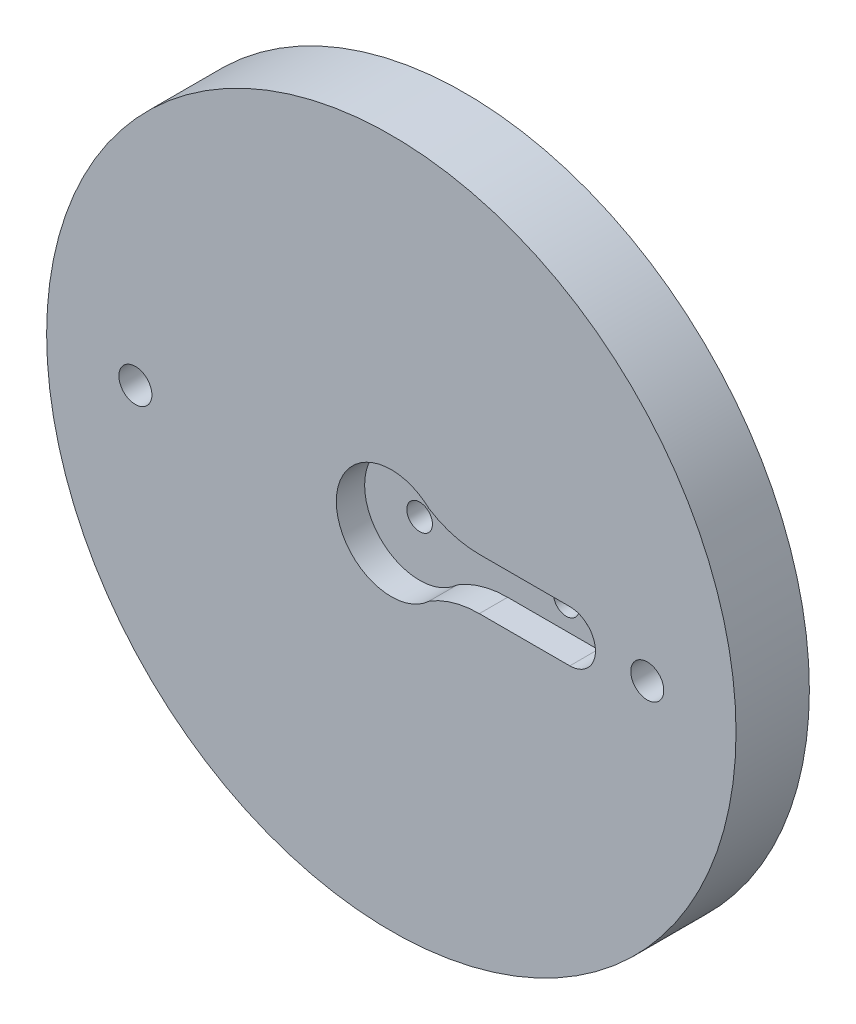
SolidWorks part; units mm, degrees
ref_plane "Front Plane" through (0, 0, 0) normal (1, 0, 0) x (0, 1, 0)
ref_plane "Top Plane" through (0, 0, 0) normal (0, 0, 1) x (0, 1, 0)
ref_plane "Right Plane" through (0, 0, 0) normal (0, 1, 0) x (-1, 0, 0)
sketch "Sketch1" plane through (0, 0, 0) normal (0, 0, 1) x (0, 1, 0)
  line L0 (0, 47) -> (0, -47) construction
  line L1 (-5.5, 0) -> (5.5, 0) construction
  circle A0 centre (0, 0) radius 47
  circle A1 centre (0, 34.897) radius 2.25
  circle A3 centre (0, -34.897) radius 2.25
  dimension "D1" = 94
  dimension "D2" = 4.5
  dimension "D3" = 34.897
extrude "Boss-Extrude1" add sketch "Sketch1" along normal blind 10
sketch "Sketch2" plane through (0, 0, 10) normal (0, 0, 1) x (1, 0, 0)
  line L0 (24.3305, 3.5) -> (12, 3.5)
  line L1 (24.3305, -3.5) -> (12, -3.5)
  line L2 (12, 3.5) -> (12, -3.5) construction
  arc A0 (5.1536, 5.4489) -> (5.1536, -5.4489) centre (0, 0) ccw
  arc A1 (12, 3.5) -> (5.1536, 5.4489) centre (12, 16.5) cw
  arc A2 (12, -3.5) -> (5.1536, -5.4489) centre (12, -16.5) ccw
  arc A3 (24.3305, -3.5) -> (24.3305, 3.5) centre (24.3305, 0) ccw
  dimension "D2" = 15
  dimension "D4" = 13
  dimension "D1" = 12
  dimension "D3" = 24.3305
extrude "Cut-Extrude1" cut sketch "Sketch2" against normal blind 3.86
sketch "Sketch3" plane through (0, 0, 6.14) normal (0, 0, 1) x (1, 0, 0)
  line L0 (-7.5, 0) -> (27.8305, 0) construction
  arc A0 (5.1536, 5.4489) -> (5.1536, -5.4489) centre (0, 0) ccw construction
  arc A1 (24.3305, -3.5) -> (24.3305, 3.5) centre (24.3305, 0) ccw construction
  circle A2 centre (0, 0) radius 1.75
  circle A3 centre (20, 0) radius 1.75
  circle A4 centre (24, 0) radius 1.75
  dimension "D1" = 3.5
  dimension "D2" = 20
  dimension "D3" = 24
extrude "Cut-Extrude2" cut sketch "Sketch3" against normal through all
